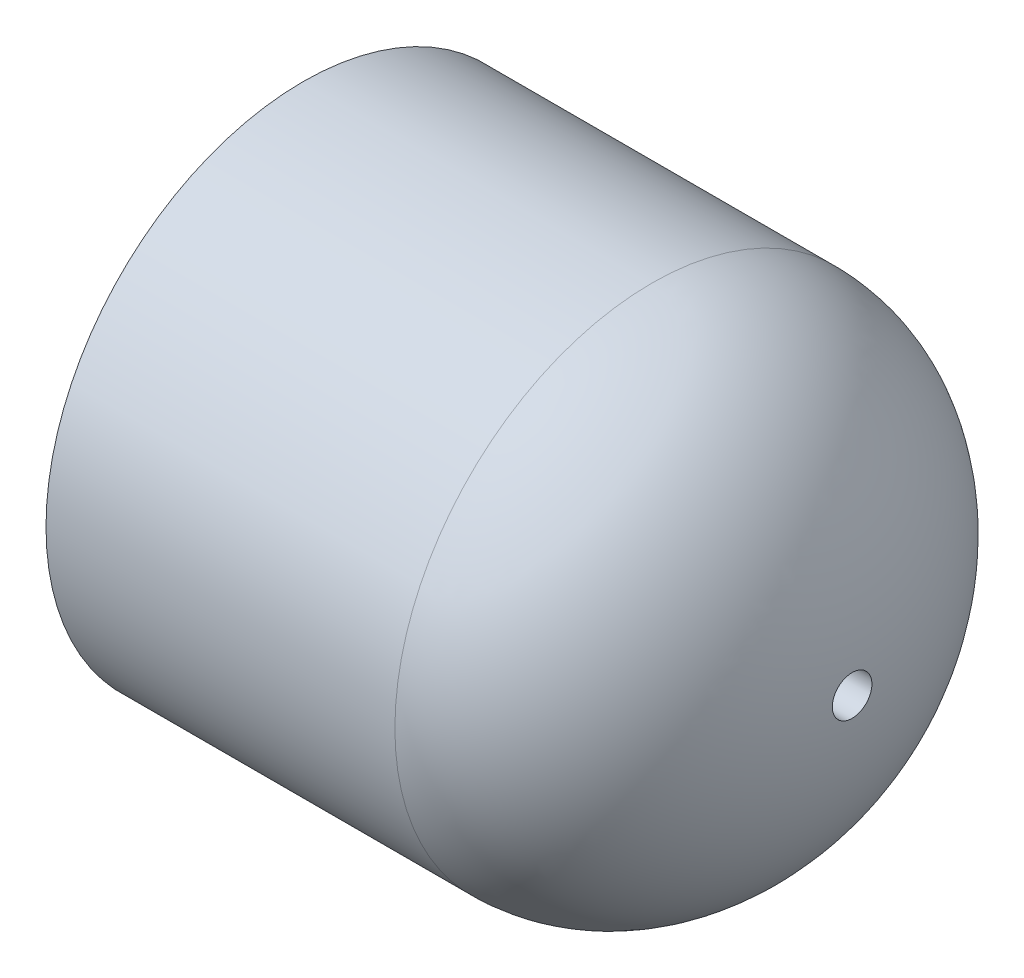
SolidWorks part; units mm, degrees
ref_plane "Front Plane" through (0, 0, 0) normal (0, 0, 1) x (1, 0, 0)
ref_plane "Top Plane" through (0, 0, 0) normal (0, 1, 0) x (1, 0, 0)
ref_plane "Right Plane" through (0, 0, 0) normal (1, 0, 0) x (0, 0, -1)
sketch "Sketch0" plane through (0, 0, 0) normal (0, 0, 1) x (1, 0, 0)
  line L3 (-22.0091, 0) -> (22.0091, 0) construction
  line L4 (-22.0091, 20.5867) -> (-22.0091, -20.5867) construction
  line L5 (5.9309, 16.637) -> (-22.0091, 16.8275) construction
  line L6 (5.9309, 16.637) -> (5.9309, -16.637) construction
  line L7 (5.9309, -16.637) -> (-22.0091, -16.8275) construction
  line L8 (-22.0091, 16.8275) -> (-22.0091, -16.8275) construction
  line L14 (5.9309, 13.3223) -> (5.9309, -13.3223) construction
  point P0 (5.9309, 0)
  dimension "H" = 16.0782
  dimension "M" = 41.1734
  dimension "OD A" = 33.655
  dimension "OD B" = 33.274
  dimension "ID" = 26.6446
  dimension "L" = 44.0182
  dimension "C" = 27.94
sketch "Sketch1" plane through (0, 0, 0) normal (0, 0, 1) x (1, 0, 0)
  line L1 (-22.0091, 0) -> (22.0091, 0) construction
  line L2 (-22.0091, 0) -> (22.0091, 0) construction
  line L3 (18.0594, 0) -> (22.0091, 0)
  line L4 (-22.0091, -20.5867) -> (-22.0091, -16.8275)
  line L5 (-22.0091, -16.8275) -> (5.9309, -16.637)
  line L6 (5.9309, -16.637) -> (5.9309, -20.5867) construction
  line L9 (5.9309, -20.5867) -> (-22.0091, -20.5867)
  ellipse E2 centre (5.9309, 0) end of major axis (5.9309, 20.5867) minor radius 16.0782 (5.9309, -20.5867) -> (22.0091, 0) ccw
  ellipse E3 centre (5.9309, 0) end of major axis (5.9309, -16.637) minor radius 12.1285 (5.9309, -16.637) -> (18.0594, 0) ccw
revolve "Revolve1" add sketch "Sketch1" angle 360 about L1
sketch "Sketch2" plane through (0, 0, 0) normal (1, 0, 0) x (0, 0, -1)
  circle A0 centre (0, 0) radius 1.5875
  dimension "D1" = 3.175
extrude "Cut-Extrude2" cut sketch "Sketch2" against normal mid plane 50.8
